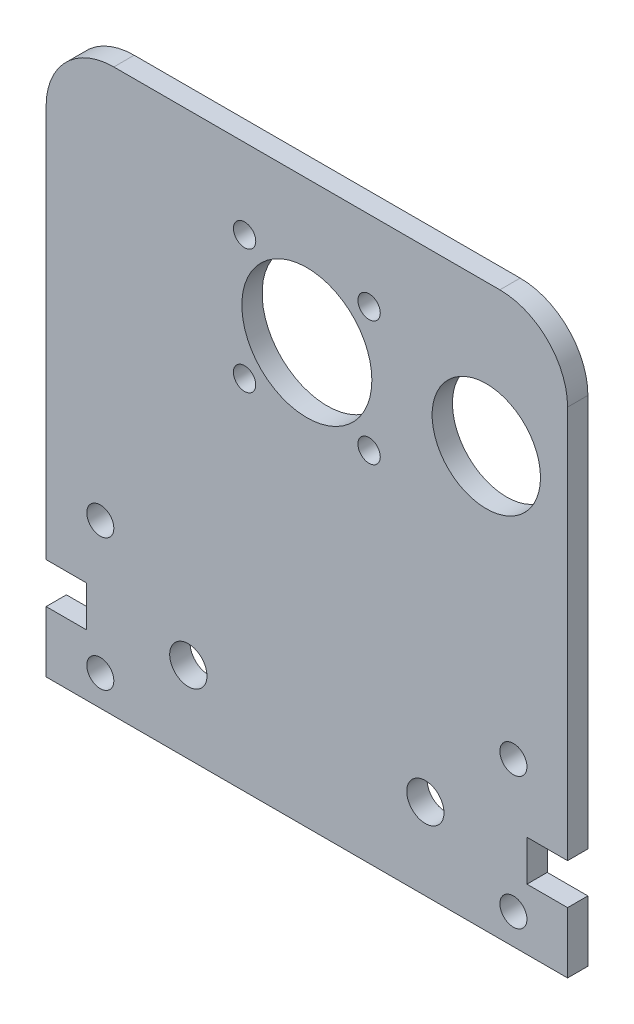
SolidWorks part; units mm, degrees
ref_plane "Front Plane" through (0, 0, 0) normal (0, 0, 1) x (1, 0, 0)
ref_plane "Top Plane" through (0, 0, 0) normal (0, 1, 0) x (1, 0, 0)
ref_plane "Right Plane" through (0, 0, 0) normal (1, 0, 0) x (0, 0, -1)
sketch "Sketch1" plane through (0, 0, 0) normal (0, 0, 1) x (1, 0, 0)
  line L0 (38.5, 12) -> (38.5, 0) construction
  line L1 (0, 0) -> (77, 0)
  line L2 (0, 0) -> (0, 12)
  line L3 (0, 12) -> (77, 12)
  line L4 (77, 0) -> (77, 12)
  line L5 (0, 9) -> (6, 9)
  line L6 (0, 9) -> (0, 3)
  line L7 (0, 3) -> (6, 3)
  line L8 (6, 9) -> (6, 3)
  line L9 (71, 9) -> (71, 3)
  line L10 (77, 3) -> (71, 3)
  line L11 (77, 9) -> (71, 9)
  line L13 (0, 12) -> (77, 12)
  line L14 (0, 12) -> (0, 77)
  line L15 (0, 77) -> (77, 77)
  line L16 (77, 12) -> (77, 77)
  point P11 (77, 3)
  dimension "D1" = 65
  dimension "D2" = 6
  dimension "D3" = 6
  dimension "D4" = 3
  dimension "D5" = 3
  dimension "D6" = 65
extrude "Boss-Extrude1" add sketch "Sketch1" along normal blind 3 contours L3 L13 L16 L15 L14 | L13 L0 L1 L4 L10 L9 L11 | L0 L3 L2 L5 L8 L7 L1
sketch "Sketch2" plane through (0, 0, 3) normal (0, 0, 1) x (1, 0, 0)
  line L0 (6, 6) -> (71, 6) construction
  line L1 (6, 9) -> (6, 3) construction
  line L2 (71, 9) -> (71, 3) construction
  circle A0 centre (21, 6) radius 2.75
  circle A1 centre (56, 6) radius 2.75
  dimension "D1" = 5.5
  dimension "D2" = 5.5
  dimension "D3" = 15
  dimension "D4" = 15
extrude "Cut-Extrude1" cut sketch "Sketch2" against normal through all
sketch "Sketch3" plane through (0, 0, 3) normal (0, 0, 1) x (1, 0, 0)
  line L0 (0, 77) -> (77, 77) construction
  line L1 (17.5, 77) -> (59.5, 77)
  line L2 (17.5, 77) -> (17.5, 35)
  line L3 (17.5, 35) -> (59.5, 35)
  line L4 (59.5, 77) -> (59.5, 35)
  line L5 (38.5, 35) -> (38.5, 77) construction
  line L6 (38.5, 0) -> (38.5, 77) construction
  line L7 (0, 0) -> (77, 0) construction
  line L8 (17.5, 77) -> (59.5, 35) construction
  line L9 (59.5, 77) -> (17.5, 35) construction
  circle A0 centre (38.5, 56) radius 9.6
  circle A1 centre (38.5, 69) radius 1.65
  circle A2 centre (47.6924, 65.1924) radius 1.65
  circle A3 centre (51.5, 56) radius 1.65
  circle A4 centre (47.6924, 46.8076) radius 1.65
  circle A5 centre (38.5, 43) radius 1.65
  circle A6 centre (29.3076, 46.8076) radius 1.65
  circle A7 centre (25.5, 56) radius 1.65
  circle A8 centre (29.3076, 65.1924) radius 1.65
  point P32 (38.5, 56)
  dimension "D3" = 19.2
  dimension "D4" = 3.3
  dimension "D1" = 42
  dimension "D2" = 42
  dimension "D5" = 13
  dimension "D6" = 8
extrude "Cut-Extrude2" cut sketch "Sketch3" against normal through all contours A6 | A4 | A2 | A8 | A0
fillet "Fillet1" radius 10 2 edges at (77, 77, 1.5) (0, 77, 1.5)
sketch "Sketch4" plane through (0, 0, 3) normal (0, 0, 1) x (1, 0, 0)
  line L0 (77, 0) -> (77, 3) construction
  line L1 (0, 0) -> (77, 0)
  line L2 (0, 0) -> (0, -6)
  line L3 (0, -6) -> (77, -6)
  line L4 (77, 0) -> (77, -6)
  dimension "D1" = 6
extrude "Boss-Extrude2" add sketch "Sketch4" against normal blind 3
sketch "Sketch5" plane through (0, 0, 3) normal (0, 0, 1) x (1, 0, 0)
  line L0 (0, 3) -> (6, 3) construction
  line L1 (77, 3) -> (71, 3) construction
  line L2 (71, 9) -> (71, 3) construction
  line L3 (6, 9) -> (6, 3) construction
  line L4 (77, 9) -> (71, 9) construction
  line L5 (0, 9) -> (6, 9) construction
  circle A0 centre (8, -1.5) radius 2
  circle A1 centre (69, -1.5) radius 2
  circle A2 centre (8, 18) radius 2
  circle A3 centre (69, 18) radius 2
  dimension "D1" = 4
  dimension "D2" = 4
  dimension "D3" = 4.5
  dimension "D4" = 4.5
  dimension "D5" = 4
  dimension "D6" = 4
  dimension "D8" = 9
  dimension "D7" = 9
extrude "Cut-Extrude3" cut sketch "Sketch5" against normal through all
ref_plane "Plane1" through (0, 6, 0) normal (0, 1, 0) x (1, 0, 0)
sketch "Sketch6" plane through (0, 0, 3) normal (0, 0, 1) x (1, 0, 0)
  line L1 (77, 9) -> (77, 67) construction
  line L2 (65, 56) -> (57, 56) construction
  line L3 (48.1, 56) -> (28.9, 56) construction
  circle A0 centre (65, 56) radius 2.5
  circle A1 centre (65, 56) radius 9
  circle A3 centre (65, 56) radius 8
  circle A4 centre (38.5, 56) radius 9.6 construction
  dimension "D1" = 5
  dimension "D2" = 18
  dimension "D3" = 16
  dimension "D5" = 12
extrude "Cut-Extrude4" cut sketch "Sketch6" against normal through all contours A0 | A3 A0
